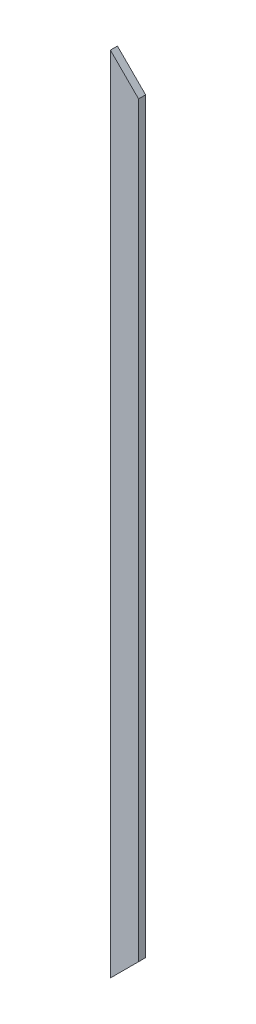
SolidWorks part; units mm, degrees
ref_plane "Plan de face" through (0, 0, 0) normal (0, 0, 1) x (1, 0, 0)
ref_plane "Plan de dessus" through (0, 0, 0) normal (0, 1, 0) x (1, 0, 0)
ref_plane "Plan de droite" through (0, 0, 0) normal (1, 0, 0) x (0, 0, -1)
sketch "Esquisse1" plane through (0, 0, 0) normal (0, 0, 1) x (1, 0, 0)
  line L0 (0, 0) -> (10, 0)
  line L1 (10, 0) -> (10, -265)
  line L2 (10, -265) -> (0, -275)
  line L3 (0, -275) -> (0, 0) construction
  line L4 (0, 0) -> (-10, 0)
  line L5 (-10, 0) -> (-10, -285)
  line L6 (-10, -285) -> (0, -275)
  dimension "D1" = 10
  dimension "D2" = 45
  dimension "D3" = 275
  dimension "D4" = 10
extrude "Boss.-Extru.1" add sketch "Esquisse1" along normal blind 5
mirror "Symétrie1" about plane through (0, 0, 5) normal (0, -1, 0) of "Boss.-Extru.1"
